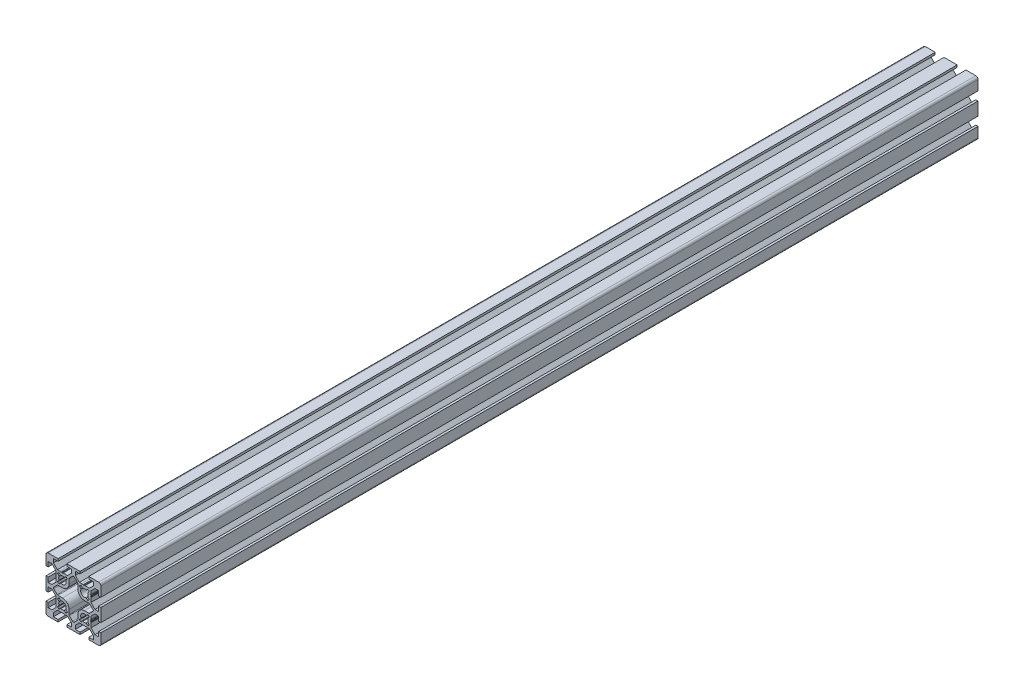
SolidWorks part; units mm, degrees
ref_plane "Front Plane" through (0, 0, 0) normal (0, 0, 1) x (1, 0, 0)
ref_plane "Top Plane" through (0, 0, 0) normal (0, 1, 0) x (1, 0, 0)
ref_plane "Right Plane" through (0, 0, 0) normal (1, 0, 0) x (0, 0, -1)
ref_plane "Plane1" through (0, 0, 0) normal (0, 0, 1) x (1, 0, 0)
sketch "Sketch1" plane through (0, 0, 0) normal (0, 0, 1) x (1, 0, 0)
  line L0 (-25, 23) -> (-25, 14)
  line L1 (-25, 14) -> (-23, 14)
  line L2 (-23, 14) -> (-23, 18.25)
  line L3 (-23, 18.25) -> (-19.6642, 18.25)
  line L4 (-19.6642, 18.25) -> (-16, 14.5858)
  line L5 (-16, 14.5858) -> (-16, 10.6536)
  line L6 (-15.933, 10.4036) -> (-15.7, 10)
  line L7 (-15.7, 10) -> (-15.933, 9.5964)
  line L8 (-15.933, 9.0964) -> (-15.751, 8.7811)
  line L9 (-15.751, 8.7811) -> (-16, 7.5)
  line L10 (-16, 7.5) -> (-16, 5.4142)
  line L11 (-16, 5.4142) -> (-19.6642, 1.75)
  line L12 (-19.6642, 1.75) -> (-23, 1.75)
  line L13 (-23, 1.75) -> (-23, 6)
  line L14 (-23, 6) -> (-25, 6)
  line L15 (-25, 6) -> (-25, -6)
  line L16 (-25, -6) -> (-23, -6)
  line L17 (-23, -6) -> (-23, -1.75)
  line L18 (-23, -1.75) -> (-19.6642, -1.75)
  line L19 (-19.6642, -1.75) -> (-16, -5.4142)
  line L20 (-16, -5.4142) -> (-16, -9.3464)
  line L21 (-15.933, -9.5964) -> (-15.7, -10)
  line L22 (-15.7, -10) -> (-15.933, -10.4036)
  line L23 (-15.933, -10.9036) -> (-15.751, -11.2189)
  line L24 (-15.751, -11.2189) -> (-16, -12.5)
  line L25 (-16, -12.5) -> (-16, -14.5858)
  line L26 (-16, -14.5858) -> (-19.6642, -18.25)
  line L27 (-19.6642, -18.25) -> (-23, -18.25)
  line L28 (-23, -18.25) -> (-23, -14)
  line L29 (-23, -14) -> (-25, -14)
  line L30 (-25, -14) -> (-25, -23)
  line L31 (-23, -25) -> (-14, -25)
  line L32 (-14, -25) -> (-14, -23)
  line L33 (-14, -23) -> (-18.25, -23)
  line L34 (-18.25, -23) -> (-18.25, -19.6642)
  line L35 (-18.25, -19.6642) -> (-14.5858, -16)
  line L36 (-14.5858, -16) -> (-10.6536, -16)
  line L37 (-10.4036, -15.933) -> (-10, -15.7)
  line L38 (-10, -15.7) -> (-9.5964, -15.933)
  line L39 (-9.0964, -15.933) -> (-8.7811, -15.751)
  line L40 (-8.7811, -15.751) -> (-7.5, -16)
  line L41 (-7.5, -16) -> (-5.4142, -16)
  line L42 (-5.4142, -16) -> (-1.75, -19.6642)
  line L43 (-1.75, -19.6642) -> (-1.75, -23)
  line L44 (-1.75, -23) -> (-6, -23)
  line L45 (-6, -23) -> (-6, -25)
  line L46 (-6, -25) -> (6, -25)
  line L47 (6, -25) -> (6, -23)
  line L48 (6, -23) -> (1.75, -23)
  line L49 (1.75, -23) -> (1.75, -19.6642)
  line L50 (1.75, -19.6642) -> (5.4142, -16)
  line L51 (5.4142, -16) -> (9.3464, -16)
  line L52 (9.5964, -15.933) -> (10, -15.7)
  line L53 (10, -15.7) -> (10.4036, -15.933)
  line L54 (10.9036, -15.933) -> (11.2189, -15.751)
  line L55 (11.2189, -15.751) -> (12.5, -16)
  line L56 (12.5, -16) -> (14.5858, -16)
  line L57 (14.5858, -16) -> (18.25, -19.6642)
  line L58 (18.25, -19.6642) -> (18.25, -23)
  line L59 (18.25, -23) -> (14, -23)
  line L60 (14, -23) -> (14, -25)
  line L61 (14, -25) -> (23, -25)
  line L62 (25, -23) -> (25, -14)
  line L63 (25, -14) -> (23, -14)
  line L64 (23, -14) -> (23, -18.25)
  line L65 (23, -18.25) -> (19.6642, -18.25)
  line L66 (19.6642, -18.25) -> (16, -14.5858)
  line L67 (16, -14.5858) -> (16, -10.6536)
  line L68 (15.933, -10.4036) -> (15.7, -10)
  line L69 (15.7, -10) -> (15.933, -9.5964)
  line L70 (15.933, -9.0964) -> (15.751, -8.7811)
  line L71 (15.751, -8.7811) -> (16, -7.5)
  line L72 (16, -7.5) -> (16, -5.4142)
  line L73 (16, -5.4142) -> (19.6642, -1.75)
  line L74 (19.6642, -1.75) -> (23, -1.75)
  line L75 (23, -1.75) -> (23, -6)
  line L76 (23, -6) -> (25, -6)
  line L77 (25, -6) -> (25, 6)
  line L78 (25, 6) -> (23, 6)
  line L79 (23, 6) -> (23, 1.75)
  line L80 (23, 1.75) -> (19.6642, 1.75)
  line L81 (19.6642, 1.75) -> (16, 5.4142)
  line L82 (16, 5.4142) -> (16, 9.3464)
  line L83 (15.933, 9.5964) -> (15.7, 10)
  line L84 (15.7, 10) -> (15.933, 10.4036)
  line L85 (15.933, 10.9036) -> (15.751, 11.2189)
  line L86 (15.751, 11.2189) -> (16, 12.5)
  line L87 (16, 12.5) -> (16, 14.5858)
  line L88 (16, 14.5858) -> (19.6642, 18.25)
  line L89 (19.6642, 18.25) -> (23, 18.25)
  line L90 (23, 18.25) -> (23, 14)
  line L91 (23, 14) -> (25, 14)
  line L92 (25, 14) -> (25, 23)
  line L93 (23, 25) -> (14, 25)
  line L94 (14, 25) -> (14, 23)
  line L95 (14, 23) -> (18.25, 23)
  line L96 (18.25, 23) -> (18.25, 19.6642)
  line L97 (18.25, 19.6642) -> (14.5858, 16)
  line L98 (14.5858, 16) -> (10.6536, 16)
  line L99 (10.4036, 15.933) -> (10, 15.7)
  line L100 (10, 15.7) -> (9.5964, 15.933)
  line L101 (9.0964, 15.933) -> (8.7811, 15.751)
  line L102 (8.7811, 15.751) -> (7.5, 16)
  line L103 (7.5, 16) -> (5.4142, 16)
  line L104 (5.4142, 16) -> (1.75, 19.6642)
  line L105 (1.75, 19.6642) -> (1.75, 23)
  line L106 (1.75, 23) -> (6, 23)
  line L107 (6, 23) -> (6, 25)
  line L108 (6, 25) -> (-6, 25)
  line L109 (-6, 25) -> (-6, 23)
  line L110 (-6, 23) -> (-1.75, 23)
  line L111 (-1.75, 23) -> (-1.75, 19.6642)
  line L112 (-1.75, 19.6642) -> (-5.4142, 16)
  line L113 (-5.4142, 16) -> (-9.3464, 16)
  line L114 (-9.5964, 15.933) -> (-10, 15.7)
  line L115 (-10, 15.7) -> (-10.4036, 15.933)
  line L116 (-10.9036, 15.933) -> (-11.2189, 15.751)
  line L117 (-11.2189, 15.751) -> (-12.5, 16)
  line L118 (-12.5, 16) -> (-14.5858, 16)
  line L119 (-14.5858, 16) -> (-18.25, 19.6642)
  line L120 (-18.25, 19.6642) -> (-18.25, 23)
  line L121 (-18.25, 23) -> (-14, 23)
  line L122 (-14, 23) -> (-14, 25)
  line L123 (-14, 25) -> (-23, 25)
  line L124 (-17.8787, -0.7071) -> (-14.8787, -3.7071)
  line L125 (-14.1716, -4) -> (-10, -4)
  line L126 (-4, -10) -> (-4, -14.1716)
  line L127 (-3.7071, -14.8787) -> (-0.7071, -17.8787)
  line L128 (0.7071, -17.8787) -> (3.7071, -14.8787)
  line L129 (4, -14.1716) -> (4, -10)
  line L130 (10, -4) -> (14.1716, -4)
  line L131 (14.8787, -3.7071) -> (17.8787, -0.7071)
  line L132 (17.8787, 0.7071) -> (14.8787, 3.7071)
  line L133 (14.1716, 4) -> (10, 4)
  line L134 (4, 10) -> (4, 14.1716)
  line L135 (3.7071, 14.8787) -> (0.7071, 17.8787)
  line L136 (-0.7071, 17.8787) -> (-3.7071, 14.8787)
  line L137 (-4, 14.1716) -> (-4, 10)
  line L138 (-10, 4) -> (-14.1716, 4)
  line L139 (-14.8787, 3.7071) -> (-17.8787, 0.7071)
  arc A0 (-16, 10.6536) -> (-15.933, 10.4036) centre (-15.5, 10.6536) ccw
  arc A1 (-15.933, 9.5964) -> (-15.933, 9.0964) centre (-15.5, 9.3464) ccw
  arc A2 (-16, -9.3464) -> (-15.933, -9.5964) centre (-15.5, -9.3464) ccw
  arc A3 (-15.933, -10.4036) -> (-15.933, -10.9036) centre (-15.5, -10.6536) ccw
  arc A4 (-25, -23) -> (-23, -25) centre (-23, -23) ccw
  arc A5 (-10.6536, -16) -> (-10.4036, -15.933) centre (-10.6536, -15.5) ccw
  arc A6 (-9.5964, -15.933) -> (-9.0964, -15.933) centre (-9.3464, -15.5) ccw
  arc A7 (9.3464, -16) -> (9.5964, -15.933) centre (9.3464, -15.5) ccw
  arc A8 (10.4036, -15.933) -> (10.9036, -15.933) centre (10.6536, -15.5) ccw
  arc A9 (23, -25) -> (25, -23) centre (23, -23) ccw
  arc A10 (16, -10.6536) -> (15.933, -10.4036) centre (15.5, -10.6536) ccw
  arc A11 (15.933, -9.5964) -> (15.933, -9.0964) centre (15.5, -9.3464) ccw
  arc A12 (16, 9.3464) -> (15.933, 9.5964) centre (15.5, 9.3464) ccw
  arc A13 (15.933, 10.4036) -> (15.933, 10.9036) centre (15.5, 10.6536) ccw
  arc A14 (25, 23) -> (23, 25) centre (23, 23) ccw
  arc A15 (10.6536, 16) -> (10.4036, 15.933) centre (10.6536, 15.5) ccw
  arc A16 (9.5964, 15.933) -> (9.0964, 15.933) centre (9.3464, 15.5) ccw
  arc A17 (-9.3464, 16) -> (-9.5964, 15.933) centre (-9.3464, 15.5) ccw
  arc A18 (-10.4036, 15.933) -> (-10.9036, 15.933) centre (-10.6536, 15.5) ccw
  arc A19 (-23, 25) -> (-25, 23) centre (-23, 23) ccw
  arc A20 (-17.8787, 0.7071) -> (-17.8787, -0.7071) centre (-17.1716, 0) ccw
  arc A21 (-14.8787, -3.7071) -> (-14.1716, -4) centre (-14.1716, -3) ccw
  arc A22 (-10, -4) -> (-4, -10) centre (-10, -10) cw
  arc A23 (-4, -14.1716) -> (-3.7071, -14.8787) centre (-3, -14.1716) ccw
  arc A24 (-0.7071, -17.8787) -> (0.7071, -17.8787) centre (0, -17.1716) ccw
  arc A25 (3.7071, -14.8787) -> (4, -14.1716) centre (3, -14.1716) ccw
  arc A26 (4, -10) -> (10, -4) centre (10, -10) cw
  arc A27 (14.1716, -4) -> (14.8787, -3.7071) centre (14.1716, -3) ccw
  arc A28 (17.8787, -0.7071) -> (17.8787, 0.7071) centre (17.1716, 0) ccw
  arc A29 (14.8787, 3.7071) -> (14.1716, 4) centre (14.1716, 3) ccw
  arc A30 (10, 4) -> (4, 10) centre (10, 10) cw
  arc A31 (4, 14.1716) -> (3.7071, 14.8787) centre (3, 14.1716) ccw
  arc A32 (0.7071, 17.8787) -> (-0.7071, 17.8787) centre (0, 17.1716) ccw
  arc A33 (-3.7071, 14.8787) -> (-4, 14.1716) centre (-3, 14.1716) ccw
  arc A34 (-4, 10) -> (-10, 4) centre (-10, 10) cw
  arc A35 (-14.1716, 4) -> (-14.8787, 3.7071) centre (-14.1716, 3) ccw
extrude "Boss-Extrude1" add sketch "Sketch1" against normal blind 800
ref_plane "Plane2" through (0, 0, 0) normal (0, 0, 1) x (1, 0, 0)
sketch "Sketch2" plane through (0, 0, 0) normal (0, 0, 1) x (1, 0, 0)
  line L0 (-14.2426, 12.8284) -> (-13.2051, 11.7909)
  line L1 (-13.2051, 8.2091) -> (-14.2426, 7.1716)
  line L2 (-14.2426, 6.4645) -> (-13.5355, 5.7574)
  line L3 (-12.8284, 5.7574) -> (-11.7909, 6.7949)
  line L4 (-6.7949, 11.7909) -> (-5.7574, 12.8284)
  line L5 (-5.7574, 13.5355) -> (-6.4645, 14.2426)
  line L6 (-7.1716, 14.2426) -> (-8.2091, 13.2051)
  line L7 (-11.7909, 13.2051) -> (-12.8284, 14.2426)
  line L8 (-13.5355, 14.2426) -> (-14.2426, 13.5355)
  arc A0 (-14.2426, 13.5355) -> (-14.2426, 12.8284) centre (-13.8891, 13.182) ccw
  arc A1 (-13.2051, 11.7909) -> (-13.1208, 11.3493) centre (-13.4879, 11.508) cw
  arc A2 (-13.1208, 11.3493) -> (-13.1208, 8.6507) centre (-10, 10) ccw
  arc A3 (-13.1208, 8.6507) -> (-13.2051, 8.2091) centre (-13.4879, 8.492) cw
  arc A4 (-14.2426, 7.1716) -> (-14.2426, 6.4645) centre (-13.8891, 6.818) ccw
  arc A5 (-13.5355, 5.7574) -> (-12.8284, 5.7574) centre (-13.182, 6.1109) ccw
  arc A6 (-11.7909, 6.7949) -> (-11.3493, 6.8792) centre (-11.508, 6.5121) cw
  arc A7 (-11.3493, 6.8792) -> (-6.8792, 11.3493) centre (-10, 10) ccw
  arc A8 (-6.8792, 11.3493) -> (-6.7949, 11.7909) centre (-6.5121, 11.508) cw
  arc A9 (-5.7574, 12.8284) -> (-5.7574, 13.5355) centre (-6.1109, 13.182) ccw
  arc A10 (-6.4645, 14.2426) -> (-7.1716, 14.2426) centre (-6.818, 13.8891) ccw
  arc A11 (-8.2091, 13.2051) -> (-8.6507, 13.1208) centre (-8.492, 13.4879) cw
  arc A12 (-8.6507, 13.1208) -> (-11.3493, 13.1208) centre (-10, 10) ccw
  arc A13 (-11.3493, 13.1208) -> (-11.7909, 13.2051) centre (-11.508, 13.4879) cw
  arc A14 (-12.8284, 14.2426) -> (-13.5355, 14.2426) centre (-13.182, 13.8891) ccw
extrude "Cut-Extrude1" cut sketch "Sketch2" against normal through all
ref_plane "Plane3" through (0, 0, 0) normal (0, 0, 1) x (1, 0, 0)
sketch "Sketch3" plane through (0, 0, 0) normal (0, 0, 1) x (1, 0, 0)
  line L0 (-12.8284, -14.2426) -> (-11.7909, -13.2051)
  line L1 (-8.2091, -13.2051) -> (-7.1716, -14.2426)
  line L2 (-6.4645, -14.2426) -> (-5.7574, -13.5355)
  line L3 (-5.7574, -12.8284) -> (-6.7949, -11.7909)
  line L4 (-11.7909, -6.7949) -> (-12.8284, -5.7574)
  line L5 (-13.5355, -5.7574) -> (-14.2426, -6.4645)
  line L6 (-14.2426, -7.1716) -> (-13.2051, -8.2091)
  line L7 (-13.2051, -11.7909) -> (-14.2426, -12.8284)
  line L8 (-14.2426, -13.5355) -> (-13.5355, -14.2426)
  arc A0 (-13.5355, -14.2426) -> (-12.8284, -14.2426) centre (-13.182, -13.8891) ccw
  arc A1 (-11.7909, -13.2051) -> (-11.3493, -13.1208) centre (-11.508, -13.4879) cw
  arc A2 (-11.3493, -13.1208) -> (-8.6507, -13.1208) centre (-10, -10) ccw
  arc A3 (-8.6507, -13.1208) -> (-8.2091, -13.2051) centre (-8.492, -13.4879) cw
  arc A4 (-7.1716, -14.2426) -> (-6.4645, -14.2426) centre (-6.818, -13.8891) ccw
  arc A5 (-5.7574, -13.5355) -> (-5.7574, -12.8284) centre (-6.1109, -13.182) ccw
  arc A6 (-6.7949, -11.7909) -> (-6.8792, -11.3493) centre (-6.5121, -11.508) cw
  arc A7 (-6.8792, -11.3493) -> (-11.3493, -6.8792) centre (-10, -10) ccw
  arc A8 (-11.3493, -6.8792) -> (-11.7909, -6.7949) centre (-11.508, -6.5121) cw
  arc A9 (-12.8284, -5.7574) -> (-13.5355, -5.7574) centre (-13.182, -6.1109) ccw
  arc A10 (-14.2426, -6.4645) -> (-14.2426, -7.1716) centre (-13.8891, -6.818) ccw
  arc A11 (-13.2051, -8.2091) -> (-13.1208, -8.6507) centre (-13.4879, -8.492) cw
  arc A12 (-13.1208, -8.6507) -> (-13.1208, -11.3493) centre (-10, -10) ccw
  arc A13 (-13.1208, -11.3493) -> (-13.2051, -11.7909) centre (-13.4879, -11.508) cw
  arc A14 (-14.2426, -12.8284) -> (-14.2426, -13.5355) centre (-13.8891, -13.182) ccw
extrude "Cut-Extrude2" cut sketch "Sketch3" against normal through all
ref_plane "Plane4" through (0, 0, 0) normal (0, 0, 1) x (1, 0, 0)
sketch "Sketch4" plane through (0, 0, 0) normal (0, 0, 1) x (1, 0, 0)
  line L0 (14.2426, -12.8284) -> (13.2051, -11.7909)
  line L1 (13.2051, -8.2091) -> (14.2426, -7.1716)
  line L2 (14.2426, -6.4645) -> (13.5355, -5.7574)
  line L3 (12.8284, -5.7574) -> (11.7909, -6.7949)
  line L4 (6.7949, -11.7909) -> (5.7574, -12.8284)
  line L5 (5.7574, -13.5355) -> (6.4645, -14.2426)
  line L6 (7.1716, -14.2426) -> (8.2091, -13.2051)
  line L7 (11.7909, -13.2051) -> (12.8284, -14.2426)
  line L8 (13.5355, -14.2426) -> (14.2426, -13.5355)
  arc A0 (14.2426, -13.5355) -> (14.2426, -12.8284) centre (13.8891, -13.182) ccw
  arc A1 (13.2051, -11.7909) -> (13.1208, -11.3493) centre (13.4879, -11.508) cw
  arc A2 (13.1208, -11.3493) -> (13.1208, -8.6507) centre (10, -10) ccw
  arc A3 (13.1208, -8.6507) -> (13.2051, -8.2091) centre (13.4879, -8.492) cw
  arc A4 (14.2426, -7.1716) -> (14.2426, -6.4645) centre (13.8891, -6.818) ccw
  arc A5 (13.5355, -5.7574) -> (12.8284, -5.7574) centre (13.182, -6.1109) ccw
  arc A6 (11.7909, -6.7949) -> (11.3493, -6.8792) centre (11.508, -6.5121) cw
  arc A7 (11.3493, -6.8792) -> (6.8792, -11.3493) centre (10, -10) ccw
  arc A8 (6.8792, -11.3493) -> (6.7949, -11.7909) centre (6.5121, -11.508) cw
  arc A9 (5.7574, -12.8284) -> (5.7574, -13.5355) centre (6.1109, -13.182) ccw
  arc A10 (6.4645, -14.2426) -> (7.1716, -14.2426) centre (6.818, -13.8891) ccw
  arc A11 (8.2091, -13.2051) -> (8.6507, -13.1208) centre (8.492, -13.4879) cw
  arc A12 (8.6507, -13.1208) -> (11.3493, -13.1208) centre (10, -10) ccw
  arc A13 (11.3493, -13.1208) -> (11.7909, -13.2051) centre (11.508, -13.4879) cw
  arc A14 (12.8284, -14.2426) -> (13.5355, -14.2426) centre (13.182, -13.8891) ccw
extrude "Cut-Extrude3" cut sketch "Sketch4" against normal through all
ref_plane "Plane5" through (0, 0, 0) normal (0, 0, 1) x (1, 0, 0)
sketch "Sketch5" plane through (0, 0, 0) normal (0, 0, 1) x (1, 0, 0)
  line L0 (12.8284, 14.2426) -> (11.7909, 13.2051)
  line L1 (8.2091, 13.2051) -> (7.1716, 14.2426)
  line L2 (6.4645, 14.2426) -> (5.7574, 13.5355)
  line L3 (5.7574, 12.8284) -> (6.7949, 11.7909)
  line L4 (11.7909, 6.7949) -> (12.8284, 5.7574)
  line L5 (13.5355, 5.7574) -> (14.2426, 6.4645)
  line L6 (14.2426, 7.1716) -> (13.2051, 8.2091)
  line L7 (13.2051, 11.7909) -> (14.2426, 12.8284)
  line L8 (14.2426, 13.5355) -> (13.5355, 14.2426)
  arc A0 (13.5355, 14.2426) -> (12.8284, 14.2426) centre (13.182, 13.8891) ccw
  arc A1 (11.7909, 13.2051) -> (11.3493, 13.1208) centre (11.508, 13.4879) cw
  arc A2 (11.3493, 13.1208) -> (8.6507, 13.1208) centre (10, 10) ccw
  arc A3 (8.6507, 13.1208) -> (8.2091, 13.2051) centre (8.492, 13.4879) cw
  arc A4 (7.1716, 14.2426) -> (6.4645, 14.2426) centre (6.818, 13.8891) ccw
  arc A5 (5.7574, 13.5355) -> (5.7574, 12.8284) centre (6.1109, 13.182) ccw
  arc A6 (6.7949, 11.7909) -> (6.8792, 11.3493) centre (6.5121, 11.508) cw
  arc A7 (6.8792, 11.3493) -> (11.3493, 6.8792) centre (10, 10) ccw
  arc A8 (11.3493, 6.8792) -> (11.7909, 6.7949) centre (11.508, 6.5121) cw
  arc A9 (12.8284, 5.7574) -> (13.5355, 5.7574) centre (13.182, 6.1109) ccw
  arc A10 (14.2426, 6.4645) -> (14.2426, 7.1716) centre (13.8891, 6.818) ccw
  arc A11 (13.2051, 8.2091) -> (13.1208, 8.6507) centre (13.4879, 8.492) cw
  arc A12 (13.1208, 8.6507) -> (13.1208, 11.3493) centre (10, 10) ccw
  arc A13 (13.1208, 11.3493) -> (13.2051, 11.7909) centre (13.4879, 11.508) cw
  arc A14 (14.2426, 12.8284) -> (14.2426, 13.5355) centre (13.8891, 13.182) ccw
extrude "Cut-Extrude4" cut sketch "Sketch5" against normal through all
